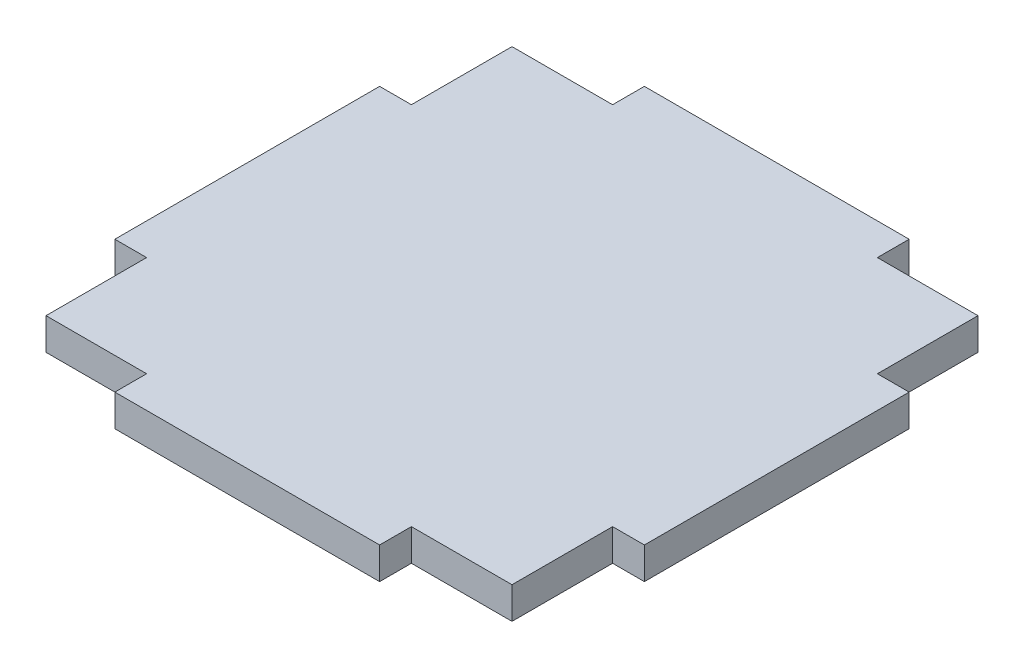
SolidWorks part; units mm, degrees
ref_plane "Plan de face" through (0, 0, 0) normal (0, 0, 1) x (1, 0, 0)
ref_plane "Plan de dessus" through (0, 0, 0) normal (0, 1, 0) x (1, 0, 0)
ref_plane "Plan de droite" through (0, 0, 0) normal (1, 0, 0) x (0, 0, -1)
sketch "Esquisse1" plane through (0, 0, 0) normal (0, 1, 0) x (1, 0, 0)
  line L1 (0, 0) -> (50, 0)
  line L2 (0, 0) -> (0, 50)
  line L3 (0, 50) -> (50, 50)
  line L4 (50, 0) -> (50, 50)
extrude "Boss.-Extru.1" add sketch "Esquisse1" along normal blind 3
sketch "Esquisse2" plane through (0, 3, 0) normal (0, 1, 0) x (1, 0, 0)
  line L0 (0, 50) -> (0, 25) construction
  line L1 (0, 50) -> (0, 0) construction
  line L2 (0, 25) -> (0, 0) construction
  line L3 (0, 0) -> (25, 0) construction
  line L4 (0, 0) -> (50, 0) construction
  line L5 (25, 0) -> (50, 0) construction
  line L6 (50, 0) -> (50, 25) construction
  line L7 (50, 0) -> (50, 50) construction
  line L8 (50, 25) -> (50, 50) construction
  line L9 (50, 50) -> (25, 50) construction
  line L10 (50, 50) -> (0, 50) construction
  line L11 (25, 50) -> (0, 50) construction
  line L12 (0, 50) -> (3, 50) construction
  line L13 (3, 50) -> (3, 47) construction
  line L14 (0, 37.5) -> (3, 37.5)
  line L15 (3, 37.5) -> (3, 47)
  line L16 (12.5, 50) -> (12.5, 47)
  line L17 (12.5, 47) -> (3, 47)
  line L18 (0, 37.5) -> (0, 50)
  line L19 (0, 50) -> (12.5, 50)
  line L20 (0, 0) -> (3, 0) construction
  line L21 (3, 0) -> (3, 3) construction
  line L22 (0, 12.5) -> (3, 12.5)
  line L23 (3, 12.5) -> (3, 3)
  line L24 (12.5, 0) -> (12.5, 3)
  line L25 (12.5, 3) -> (3, 3)
  line L26 (0, 12.5) -> (0, 0)
  line L27 (0, 0) -> (12.5, 0)
  line L28 (50, 0) -> (47, 0) construction
  line L29 (47, 0) -> (47, 3) construction
  line L30 (50, 12.5) -> (47, 12.5)
  line L31 (47, 12.5) -> (47, 3)
  line L32 (37.5, 0) -> (37.5, 3)
  line L33 (37.5, 3) -> (47, 3)
  line L34 (37.5, 0) -> (50, 0)
  line L35 (50, 0) -> (50, 12.5)
  line L36 (50, 50) -> (47, 50) construction
  line L37 (47, 50) -> (47, 47) construction
  line L38 (37.5, 50) -> (37.5, 47)
  line L39 (37.5, 47) -> (47, 47)
  line L40 (50, 37.5) -> (47, 37.5)
  line L41 (47, 37.5) -> (47, 47)
  line L42 (37.5, 50) -> (50, 50)
  line L43 (50, 50) -> (50, 37.5)
extrude "Enlèv. mat.-Extru.1" cut sketch "Esquisse2" against normal blind 3
